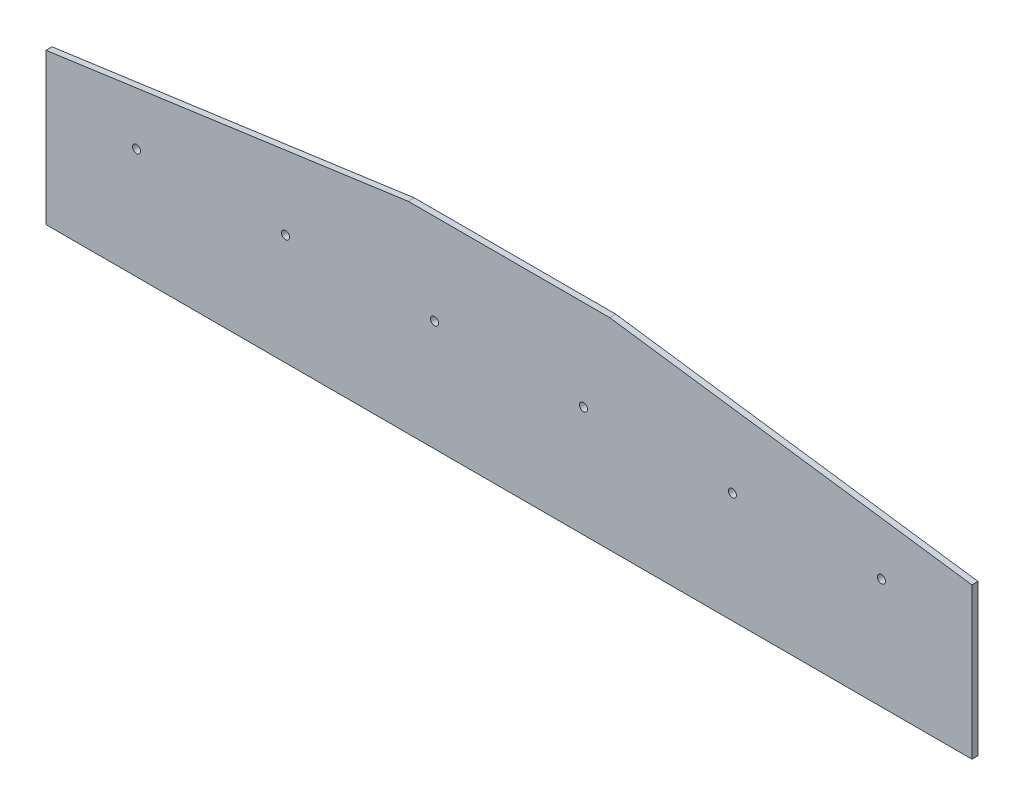
SolidWorks part; units mm, degrees
ref_plane "Ön Düzlem" through (0, 0, 0) normal (0, 0, 1) x (1, 0, 0)
ref_plane "Üst Düzlem" through (0, 0, 0) normal (0, 1, 0) x (1, 0, 0)
ref_plane "Sağ Düzlem" through (0, 0, 0) normal (1, 0, 0) x (0, 0, -1)
sketch "Çizim1" plane through (0, 0, 0) normal (0, 0, 1) x (1, 0, 0)
  line L0 (230, 0) -> (230, 100) construction
  line L1 (0, 0) -> (460, 0)
  line L2 (0, 0) -> (0, 75)
  line L3 (0, 55) -> (460, 55) construction
  line L4 (460, 0) -> (460, 75)
  line L5 (0, 75) -> (180, 100)
  line L6 (180, 100) -> (280, 100)
  line L7 (280, 100) -> (460, 75)
  circle A0 centre (45, 55) radius 2
  circle A1 centre (119, 55) radius 2
  circle A2 centre (193, 55) radius 2
  circle A3 centre (267, 55) radius 2
  circle A4 centre (341, 55) radius 2
  circle A5 centre (415, 55) radius 2
  dimension "D8" = 4
  dimension "D11" = 74
  dimension "D1" = 460
  dimension "D2" = 75
  dimension "D3" = 100
  dimension "D4" = 100
  dimension "D5" = 75
  dimension "D6" = 100
  dimension "D7" = 55
  dimension "D9" = 45
  dimension "D10" = 6
extrude "Yükseklik-Ekstrüzyon1" add sketch "Çizim1" along normal blind 3
